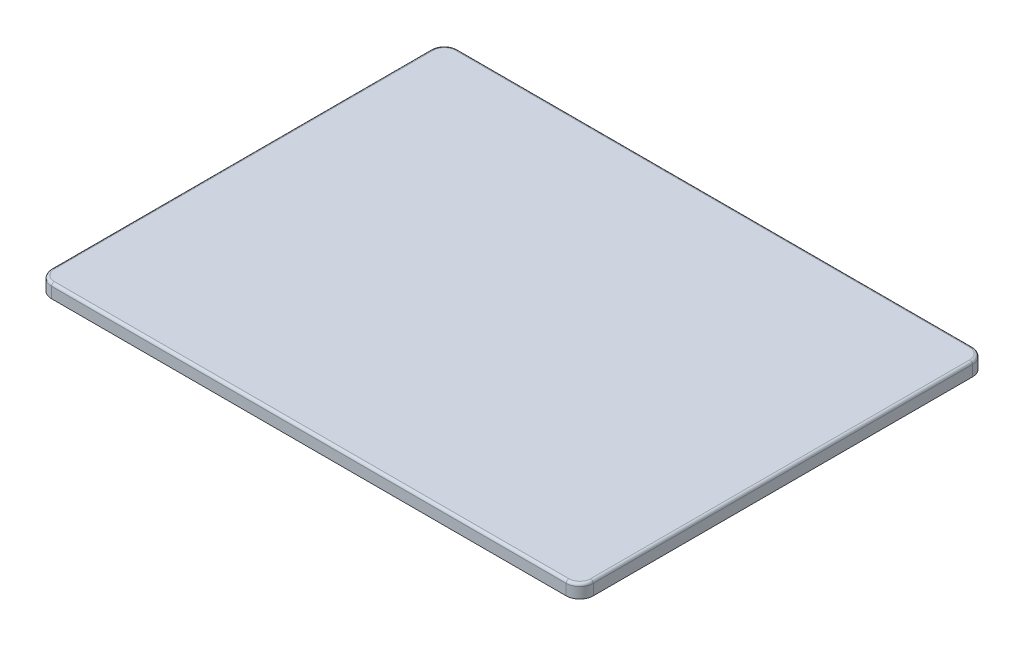
SolidWorks part; units mm, degrees
material "AISI Type 316L stainless steel"
ref_plane "Front Plane" through (0, 0, 0) normal (0, 0, 1) x (1, 0, 0)
ref_plane "Top Plane" through (0, 0, 0) normal (0, 1, 0) x (1, 0, 0)
ref_plane "Right Plane" through (0, 0, 0) normal (1, 0, 0) x (0, 0, -1)
sketch "Sketch1" plane through (0, 0, 0) normal (0, 1, 0) x (1, 0, 0)
  line L1 (-25.4, 19.05) -> (25.4, 19.05)
  line L2 (-25.4, 19.05) -> (-25.4, -19.05)
  line L3 (-25.4, -19.05) -> (25.4, -19.05)
  line L4 (25.4, 19.05) -> (25.4, -19.05)
  line L5 (-25.4, 19.05) -> (25.4, -19.05) construction
  line L6 (-25.4, -19.05) -> (25.4, 19.05) construction
  point P0 (0, 0)
  dimension "D1" = 50.8
  dimension "D2" = 38.1
extrude "Boss-Extrude1" add sketch "Sketch1" along normal blind 1.27
fillet "Fillet1" radius 1.27 4 edges at (25.4, 0.635, 19.05) (25.4, 0.635, -19.05) (-25.4, 0.635, -19.05) (-25.4, 0.635, 19.05)
fillet "Fillet2" radius 0.254 8 edges at (-25.028, 1.27, 18.678) (-25.4, 1.27, 0) (-25.028, 1.27, -18.678) (0, 1.27, -19.05) (25.028, 1.27, -18.678) (25.4, 1.27, 0) (25.028, 1.27, 18.678) (0, 1.27, 19.05)
